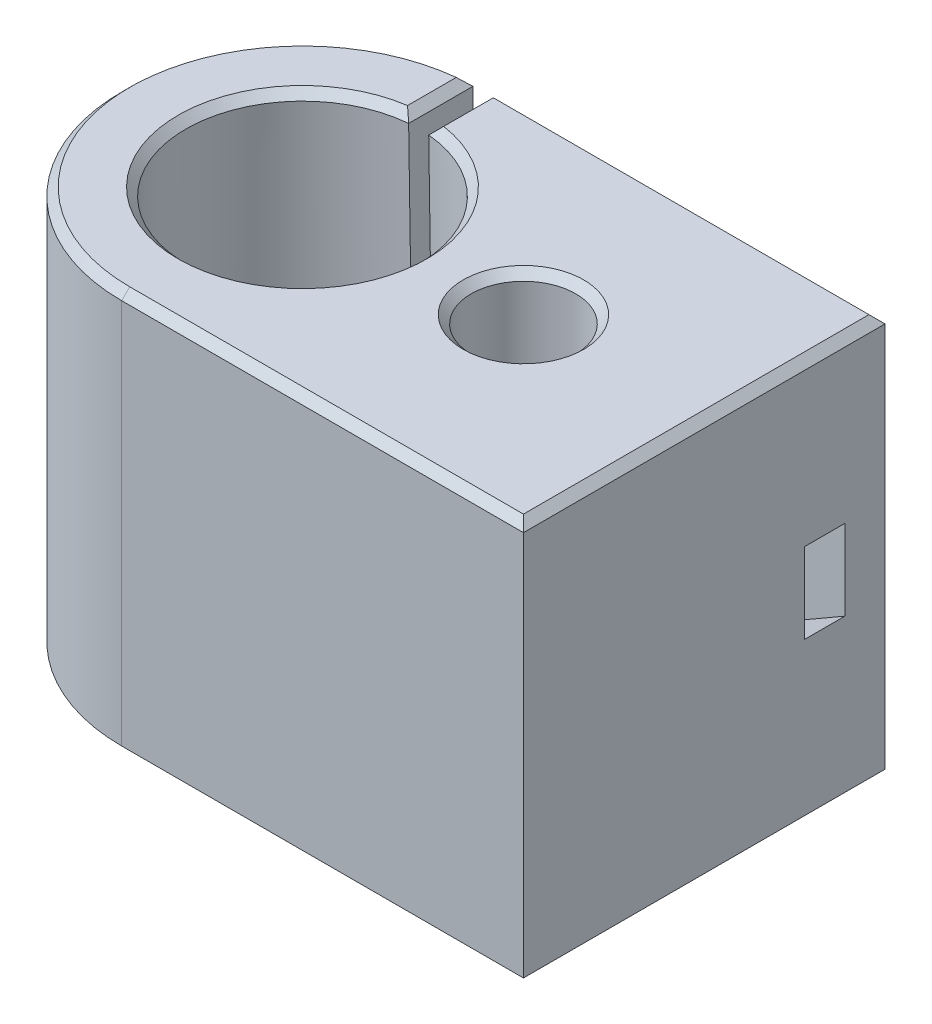
SolidWorks part; units mm, degrees
ref_plane "Front Plane" through (0, 0, 0) normal (0, 0, 1) x (1, 0, 0)
ref_plane "Top Plane" through (0, 0, 0) normal (0, 1, 0) x (1, 0, 0)
ref_plane "Right Plane" through (0, 0, 0) normal (1, 0, 0) x (0, 0, -1)
sketch "Sketch1" plane through (0, 0, 0) normal (0, 1, 0) x (1, 0, 0)
  line L0 (0, 9) -> (20, 9)
  line L1 (20, 9) -> (20, -9)
  line L2 (20, -9) -> (0, -9)
  line L3 (20, 0) -> (0, 0) construction
  arc A1 (0, 9) -> (0, -9) centre (0, 0) ccw
  dimension "D2" = 18
  dimension "D3" = 18
  dimension "D4" = 11
extrude "Boss-Extrude1" add sketch "Sketch1" along normal blind 20
sketch "Sketch3" plane through (0, 0, 9) normal (0, 0, 1) x (1, 0, 0)
  line L0 (17, 19.1571) -> (17, 16.8584)
  line L1 (17, 16.0155) -> (17, 13.7168)
  line L2 (17, 12.8739) -> (17, 10.5752)
  line L3 (17, 9.7323) -> (17, 7.4336)
  line L4 (17, 6.5907) -> (17, 4.292)
  line L5 (17, 3.4491) -> (17, 1.1504)
  line L29 (5, 20) -> (5, 0)
  line L30 (5, 0) -> (16.155, 0)
  line L31 (16.155, 0) -> (17, 0.3075)
  line L32 (17, 0.3075) -> (17, 1.1504)
  line L33 (17, 1.1504) -> (14.8795, 1.9222)
  line L34 (14.7492, 2.1083) -> (14.7492, 2.4912)
  line L35 (14.8795, 2.6774) -> (17, 3.4491)
  line L36 (17, 3.4491) -> (17, 4.292)
  line L37 (17, 4.292) -> (14.8795, 5.0638)
  line L38 (14.7492, 5.2499) -> (14.7492, 5.6328)
  line L39 (14.8795, 5.819) -> (17, 6.5907)
  line L40 (17, 6.5907) -> (17, 7.4336)
  line L41 (17, 7.4336) -> (14.8795, 8.2054)
  line L42 (14.7492, 8.3915) -> (14.7492, 8.7744)
  line L43 (14.8795, 8.9606) -> (17, 9.7323)
  line L44 (17, 9.7323) -> (17, 10.5752)
  line L45 (17, 10.5752) -> (14.8795, 11.347)
  line L46 (14.7492, 11.5331) -> (14.7492, 11.916)
  line L47 (14.8795, 12.1022) -> (17, 12.8739)
  line L48 (17, 12.8739) -> (17, 13.7168)
  line L49 (17, 13.7168) -> (14.8795, 14.4886)
  line L50 (14.7492, 14.6747) -> (14.7492, 15.0576)
  line L51 (14.8795, 15.2438) -> (17, 16.0155)
  line L52 (17, 16.0155) -> (17, 16.8584)
  line L53 (17, 16.8584) -> (14.8795, 17.6302)
  line L54 (14.7492, 17.8163) -> (14.7492, 18.1992)
  line L55 (14.8795, 18.3854) -> (17, 19.1571)
  line L56 (17, 19.1571) -> (17, 20)
  line L57 (17, 20) -> (5, 20)
  line L62 (17, 1.1504) -> (14.8795, 1.9222)
  line L63 (14.7492, 2.1083) -> (14.7492, 2.4912)
  line L64 (14.8795, 2.6774) -> (17, 3.4491)
  line L66 (17, 4.292) -> (14.8795, 5.0638)
  line L67 (14.7492, 5.2499) -> (14.7492, 5.6328)
  line L68 (14.8795, 5.819) -> (17, 6.5907)
  line L70 (17, 7.4336) -> (14.8795, 8.2054)
  line L71 (14.7492, 8.3915) -> (14.7492, 8.7744)
  line L72 (14.8795, 8.9606) -> (17, 9.7323)
  line L74 (17, 10.5752) -> (14.8795, 11.347)
  line L75 (14.7492, 11.5331) -> (14.7492, 11.916)
  line L76 (14.8795, 12.1022) -> (17, 12.8739)
  line L78 (17, 13.7168) -> (14.8795, 14.4886)
  line L79 (14.7492, 14.6747) -> (14.7492, 15.0576)
  line L80 (14.8795, 15.2438) -> (17, 16.0155)
  line L82 (17, 16.8584) -> (14.8795, 17.6302)
  line L83 (14.7492, 17.8163) -> (14.7492, 18.1992)
  line L84 (14.8795, 18.3854) -> (17, 19.1571)
  arc A12 (14.7492, 2.1083) -> (14.8795, 1.9222) centre (14.9473, 2.1083) ccw
  arc A13 (14.8795, 2.6774) -> (14.7492, 2.4912) centre (14.9473, 2.4912) ccw
  arc A14 (14.7492, 5.2499) -> (14.8795, 5.0638) centre (14.9473, 5.2499) ccw
  arc A15 (14.8795, 5.819) -> (14.7492, 5.6328) centre (14.9473, 5.6328) ccw
  arc A16 (14.7492, 8.3915) -> (14.8795, 8.2054) centre (14.9473, 8.3915) ccw
  arc A17 (14.8795, 8.9606) -> (14.7492, 8.7744) centre (14.9473, 8.7744) ccw
  arc A18 (14.7492, 11.5331) -> (14.8795, 11.347) centre (14.9473, 11.5331) ccw
  arc A19 (14.8795, 12.1022) -> (14.7492, 11.916) centre (14.9473, 11.916) ccw
  arc A20 (14.7492, 14.6747) -> (14.8795, 14.4886) centre (14.9473, 14.6747) ccw
  arc A21 (14.8795, 15.2438) -> (14.7492, 15.0576) centre (14.9473, 15.0576) ccw
  arc A22 (14.7492, 17.8163) -> (14.8795, 17.6302) centre (14.9473, 17.8163) ccw
  arc A23 (14.8795, 18.3854) -> (14.7492, 18.1992) centre (14.9473, 18.1992) ccw
  arc A24 (14.7492, 2.1083) -> (14.8795, 1.9222) centre (14.9473, 2.1083) ccw
  arc A25 (14.8795, 2.6774) -> (14.7492, 2.4912) centre (14.9473, 2.4912) ccw
  arc A26 (14.7492, 5.2499) -> (14.8795, 5.0638) centre (14.9473, 5.2499) ccw
  arc A27 (14.8795, 5.819) -> (14.7492, 5.6328) centre (14.9473, 5.6328) ccw
  arc A28 (14.7492, 8.3915) -> (14.8795, 8.2054) centre (14.9473, 8.3915) ccw
  arc A29 (14.8795, 8.9606) -> (14.7492, 8.7744) centre (14.9473, 8.7744) ccw
  arc A30 (14.7492, 11.5331) -> (14.8795, 11.347) centre (14.9473, 11.5331) ccw
  arc A31 (14.8795, 12.1022) -> (14.7492, 11.916) centre (14.9473, 11.916) ccw
  arc A32 (14.7492, 14.6747) -> (14.8795, 14.4886) centre (14.9473, 14.6747) ccw
  arc A33 (14.8795, 15.2438) -> (14.7492, 15.0576) centre (14.9473, 15.0576) ccw
  arc A34 (14.7492, 17.8163) -> (14.8795, 17.6302) centre (14.9473, 17.8163) ccw
  arc A35 (14.8795, 18.3854) -> (14.7492, 18.1992) centre (14.9473, 18.1992) ccw
  dimension "D1" = 0
extrude "Cut-Extrude1" [suppressed] cut sketch "Sketch3" against normal up to surface (10 mm away)
sketch "Sketch7" plane through (0, 0, 0) normal (0, 0, 1) x (1, 0, 0)
  line L0 (0, 0) -> (-6.1, 0)
  line L1 (-6.1, 0) -> (-5.8, 20)
  line L2 (0, 20) -> (-9, 20) construction
  line L3 (-5.8, 20) -> (0, 20)
  line L4 (0, 20) -> (0, 0)
  line L5 (0, 20) -> (0, 21.3536) construction
  dimension "D1" = 12.2
  dimension "D2" = 11.6
revolve "Cut-Revolve1" cut sketch "Sketch7" angle 360 about L5
sketch "Sketch4" plane through (0, 20, 0) normal (0, 1, 0) x (1, 0, 0)
  line L1 (-0.5, 9) -> (0.5, 9)
  line L2 (-0.5, 9) -> (-0.5, 0)
  line L3 (-0.5, 0) -> (0.5, 0)
  line L4 (0.5, 9) -> (0.5, 0)
  arc A0 (0, 9) -> (0, -9) centre (0, 0) ccw construction
  dimension "D1" = 1
extrude "Cut-Extrude2" cut sketch "Sketch4" against normal up to surface (20 mm away) up to face at (6.1, 0, 0)
sketch "Sketch5" plane through (0, 20, 0) normal (0, 1, 0) x (1, 0, 0)
  circle A0 centre (11, 0) radius 2.6
  point P7 (11, 0)
  dimension "D1" = 5.2
  dimension "D2" = 11
sketch "Sketch6" plane through (0, 0, -9) normal (0, 0, -1) x (-1, 0, 0)
  line L0 (-20, 12) -> (-14, 15.4641)
  line L1 (-20, 20) -> (-20, 0) construction
  line L2 (-14, 4.5359) -> (-20, 8)
  line L3 (-14, 10) -> (-20, 10) construction
  line L4 (-20, 12) -> (-20, 8)
  line L5 (-14, 4.5359) -> (-14, 15.4641)
  line L6 (-20, 20) -> (-0.5, 20) construction
  dimension "D1" = 4
  dimension "D2" = 30
  dimension "D3" = 6
  dimension "D4" = 30
  dimension "D5" = 10
extrude "Cut-Extrude4" cut sketch "Sketch6" against normal blind 2 from offset 2 offset against normal yes
extrude "Cut-Extrude5" cut sketch "Sketch5" against normal up to surface (20 mm away) up to face at (4.4648, 0, -1.2461)
chamfer "Chamfer1" distance 0.4 angle 45 16 edges at (0, 0, 6.1) (0.5, 0, -7.5397) (10.25, 0, -9) (20, 0, 0) (10, 0, 9) (-0.5, 0, -7.5328) (-8.9965, 0, 0.2501) (11, 0, 2.6) (0, 20, 5.8) (0.5, 20, -7.3892) (10.25, 20, -9) (20, 20, 0) (10, 20, 9) (-8.9965, 20, 0.2501) (-0.5, 20, -7.3823) (11, 20, 2.6)
